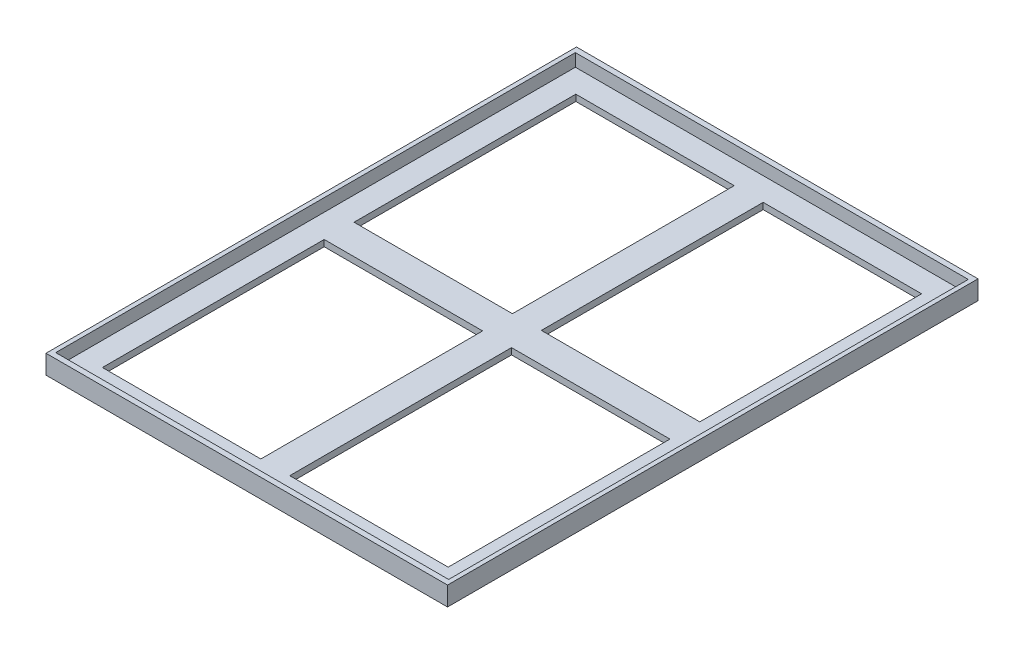
SolidWorks part; units mm, degrees
ref_plane "Alzado" through (0, 0, 0) normal (0, 0, 1) x (1, 0, 0)
ref_plane "Planta" through (0, 0, 0) normal (0, 1, 0) x (1, 0, 0)
ref_plane "Vista lateral" through (0, 0, 0) normal (1, 0, 0) x (0, 0, -1)
sketch "Croquis1" plane through (0, 0, 0) normal (0, 1, 0) x (1, 0, 0)
  line L1 (-310, 410) -> (310, 410)
  line L2 (-310, 410) -> (-310, -410)
  line L3 (-310, -410) -> (310, -410)
  line L4 (310, 410) -> (310, -410)
  line L5 (-310, 410) -> (310, -410) construction
  line L6 (-310, -410) -> (310, 410) construction
  point P0 (0, 0)
  dimension "D1" = 820
  dimension "D2" = 620
extrude "Saliente-Extruir1" add sketch "Croquis1" along normal blind 10
sketch "Croquis2" plane through (0, 10, 0) normal (0, 1, 0) x (1, 0, 0)
  line L1 (-316.8125, 418.5379) -> (316.8125, 418.5379)
  line L2 (-316.8125, 418.5379) -> (-316.8125, -418.5379)
  line L3 (-316.8125, -418.5379) -> (316.8125, -418.5379)
  line L4 (316.8125, 418.5379) -> (316.8125, -418.5379)
  line L5 (-316.8125, 418.5379) -> (316.8125, -418.5379) construction
  line L6 (-316.8125, -418.5379) -> (316.8125, 418.5379) construction
  line L7 (-310, 410) -> (310, 410)
  line L8 (-310, 410) -> (-310, -410)
  line L9 (-310, -410) -> (310, -410)
  line L10 (310, 410) -> (310, -410)
  line L11 (-310, 410) -> (310, -410) construction
  line L12 (-310, -410) -> (310, 410) construction
  point P0 (0, 0)
  point P6 (0, 0)
  point P12 (310.2479, -410.3122)
  point P13 (313.2567, -413.7015)
  point P14 (316.7119, -418.662)
  point P15 (316.8125, -418.5379)
extrude "Saliente-Extruir2" add sketch "Croquis2" along normal blind 20 separate body
sketch "Croquis3" plane through (0, 10, 0) normal (0, -1, 0) x (1, 0, 0)
  line L1 (-316.8125, 418.5379) -> (316.8125, 418.5379)
  line L2 (-316.8125, 418.5379) -> (-316.8125, -418.5379)
  line L3 (-316.8125, -418.5379) -> (316.8125, -418.5379)
  line L4 (316.8125, 418.5379) -> (316.8125, -418.5379)
  line L5 (-316.8125, 418.5379) -> (316.8125, -418.5379) construction
  line L6 (-316.8125, -418.5379) -> (316.8125, 418.5379) construction
  point P0 (0, 0)
extrude "Saliente-Extruir3" add sketch "Croquis3" along normal blind 10
sketch "Croquis4" plane through (0, 0, 0) normal (0, -1, 0) x (1, 0, 0)
  line L0 (-22.8125, 373.5379) -> (-272.8125, 373.5379)
  line L1 (272.8125, 373.5379) -> (22.8125, 373.5379)
  line L2 (272.8125, 373.5379) -> (272.8125, 23.5379)
  line L3 (272.8125, 23.5379) -> (22.8125, 23.5379)
  line L4 (22.8125, 373.5379) -> (22.8125, 23.5379)
  line L5 (272.8125, 373.5379) -> (22.8125, 23.5379) construction
  line L6 (272.8125, 23.5379) -> (22.8125, 373.5379) construction
  line L7 (-22.8125, 373.5379) -> (-22.8125, 23.5379)
  line L8 (-22.8125, 23.5379) -> (-272.8125, 23.5379)
  line L9 (-272.8125, 373.5379) -> (-272.8125, 23.5379)
  line L10 (-22.8125, 373.5379) -> (-272.8125, 23.5379) construction
  line L11 (-22.8125, 23.5379) -> (-272.8125, 373.5379) construction
  line L12 (-22.8125, -23.5379) -> (-272.8125, -23.5379)
  line L13 (-22.8125, -23.5379) -> (-22.8125, -373.5379)
  line L14 (-22.8125, -373.5379) -> (-272.8125, -373.5379)
  line L15 (-272.8125, -23.5379) -> (-272.8125, -373.5379)
  line L16 (-22.8125, -23.5379) -> (-272.8125, -373.5379) construction
  line L17 (-22.8125, -373.5379) -> (-272.8125, -23.5379) construction
  line L18 (272.8125, -23.5379) -> (22.8125, -23.5379)
  line L19 (272.8125, -23.5379) -> (272.8125, -373.5379)
  line L20 (272.8125, -373.5379) -> (22.8125, -373.5379)
  line L21 (22.8125, -23.5379) -> (22.8125, -373.5379)
  line L22 (272.8125, -23.5379) -> (22.8125, -373.5379) construction
  line L23 (272.8125, -373.5379) -> (22.8125, -23.5379) construction
  line L24 (-316.8125, 418.5379) -> (-316.8125, -418.5379) construction
  line L25 (316.8125, -418.5379) -> (316.8125, 418.5379) construction
  line L26 (-316.8125, -418.5379) -> (316.8125, -418.5379) construction
  line L27 (316.8125, 418.5379) -> (-316.8125, 418.5379) construction
  point P0 (147.8125, 198.5379)
  point P5 (0, 0)
  point P6 (0, 0)
  point P7 (0, 0)
  point P8 (-147.8125, 198.5379)
  point P13 (-147.8125, -198.5379)
  point P18 (147.8125, -198.5379)
  dimension "D1" = 350
  dimension "D2" = 250
  dimension "D3" = 350
  dimension "D4" = 250
  dimension "D5" = 350
  dimension "D6" = 250
  dimension "D7" = 350
  dimension "D8" = 250
  dimension "D9" = 44
  dimension "D10" = 44
  dimension "D11" = 44
  dimension "D12" = 44
  dimension "D13" = 45
  dimension "D14" = 45
extrude "Cortar-Extruir1" cut sketch "Croquis4" against normal blind 10
